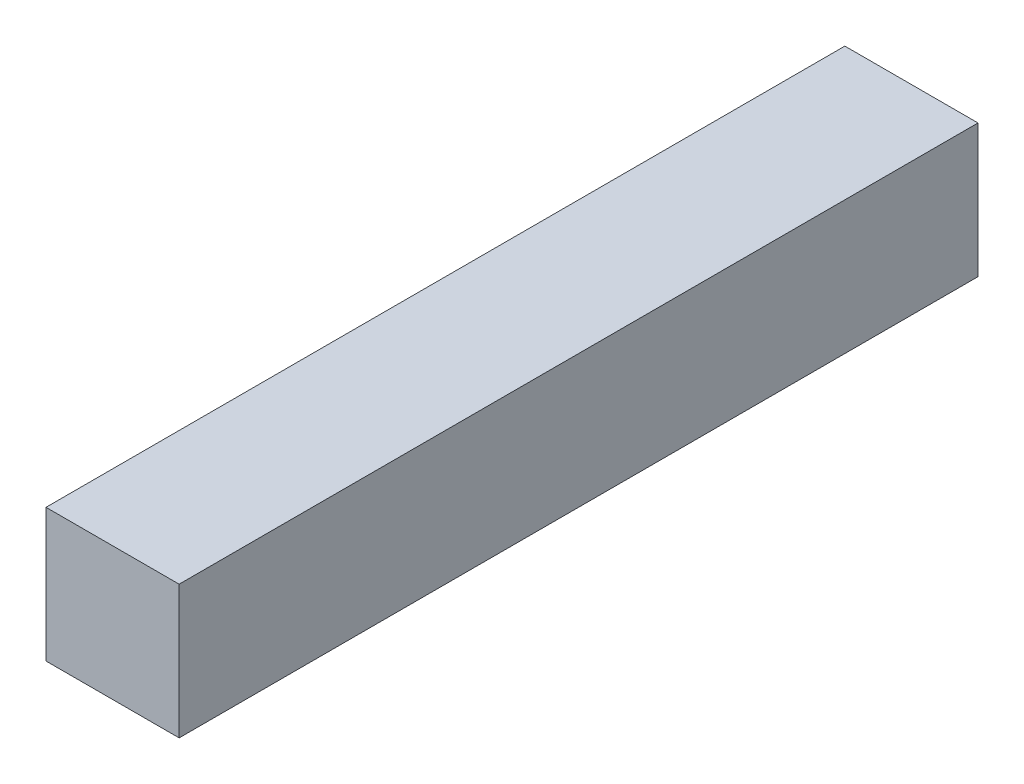
SolidWorks part; units mm, degrees
ref_plane "Front Plane" through (0, 0, 0) normal (0, 0, 1) x (1, 0, 0)
ref_plane "Top Plane" through (0, 0, 0) normal (0, 1, 0) x (1, 0, 0)
ref_plane "Right Plane" through (0, 0, 0) normal (1, 0, 0) x (0, 0, -1)
sketch "Sketch1" plane through (0, 0, 0) normal (0, 0, 1) x (1, 0, 0)
  line L1 (0, 0) -> (5, 0)
  line L2 (0, 0) -> (0, 5)
  line L3 (0, 5) -> (5, 5)
  line L4 (5, 0) -> (5, 5)
  dimension "D1" = 5
  dimension "D2" = 5
extrude "Boss-Extrude1" add sketch "Sketch1" along normal blind 30
